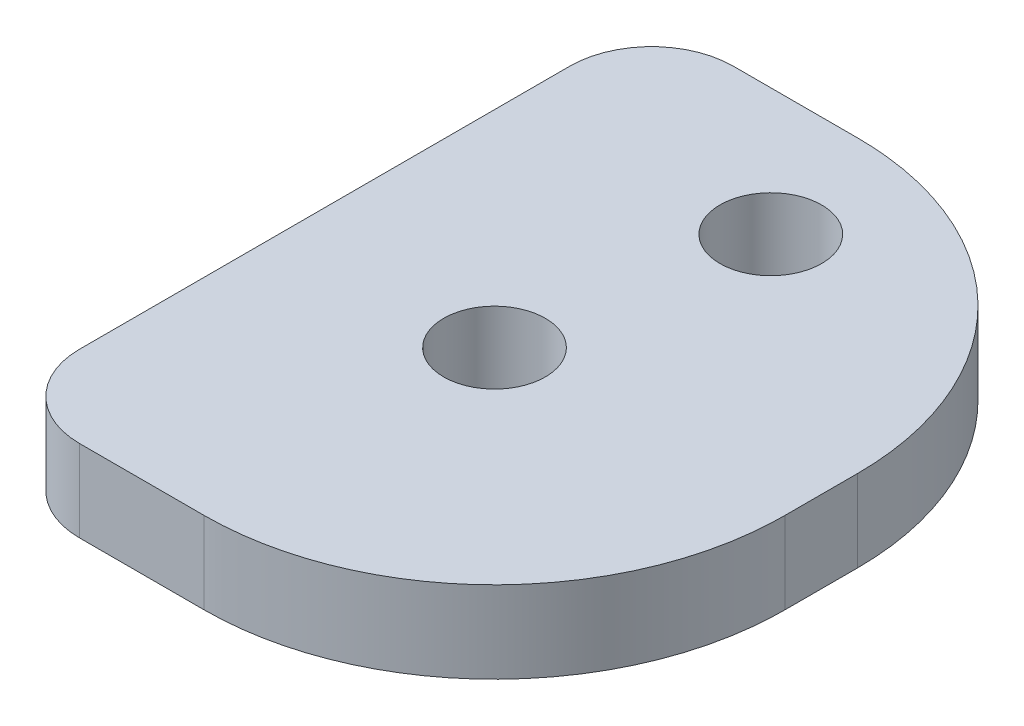
SolidWorks part; units mm, degrees
ref_plane "Front Plane" through (0, 0, 0) normal (0, 0, 1) x (1, 0, 0)
ref_plane "Top Plane" through (0, 0, 0) normal (0, 1, 0) x (1, 0, 0)
ref_plane "Right Plane" through (0, 0, 0) normal (1, 0, 0) x (0, 0, -1)
sketch "Sketch1" plane through (0, 0, 0) normal (0, 1, 0) x (1, 0, 0)
  line L1 (-25.4, 11.43) -> (25.4, 11.43)
  line L2 (-25.4, 11.43) -> (-25.4, -11.43)
  line L3 (-25.4, -11.43) -> (25.4, -11.43)
  line L4 (25.4, 11.43) -> (25.4, -11.43)
  dimension "D1" = 22.86
  dimension "D2" = 50.8
  dimension "D3" = 11.43
  dimension "D4" = 25.4
extrude "Boss-Extrude1" add sketch "Sketch1" along normal blind 3.175
fillet "Fillet1" radius 10.16 2 edges at (-25.4, 1.5875, 11.43) (25.4, 1.5875, 11.43)
sketch "Sketch3" plane through (0, 3.175, 0) normal (0, 1, 0) x (1, 0, 0)
  line L0 (-7.7526, -1.27) -> (18.5521, -1.27) construction
  circle A0 centre (15.24, -1.27) radius 1.778
  circle A1 centre (16.637, 6.9948) radius 1.778
  arc A2 (15.24, -11.43) -> (25.4, -1.27) centre (15.24, -1.27) ccw construction
  circle A3 centre (-3.81, -1.27) radius 1.778
  dimension "D1" = 3.556
  dimension "D2" = 3.556
  dimension "D6" = 3.556
  dimension "D3" = 8.382
  dimension "D4" = 1.397
  dimension "D5" = 19.05
extrude "Cut-Extrude1" cut sketch "Sketch3" against normal through all
fillet "Fillet3" radius 10.16 2 edges at (-25.4, 1.5875, -11.43) (25.4, 1.5875, -11.43)
scale "Scale1" scale about centroid uniform scaling no x scale factor 1.11 y scale factor 1 z scale factor 1.11
sketch "Sketch4" plane through (0, 3.175, 0) normal (0, 1, 0) x (1, 0, 0)
  line L1 (16.9458, 12.692) -> (-16.887, 12.692) construction
  line L2 (8.9448, 9.517) -> (8.9448, -9.5076) construction
  line L4 (-28.1646, 1.4144) -> (-28.1646, -1.405) construction
  line L5 (8.9448, 12.692) -> (-28.1646, 12.692)
  line L6 (8.9448, 12.692) -> (8.9448, -12.6826)
  line L7 (8.9448, -12.6826) -> (-28.1646, -12.6826)
  line L8 (-28.1646, 12.692) -> (-28.1646, -12.6826)
  line L9 (-16.887, -12.6826) -> (16.9458, -12.6826) construction
extrude "Cut-Extrude2" cut sketch "Sketch4" against normal through all contours L5 L8 L7 L6
fillet "Fillet4" radius 3.175 2 edges at (8.9448, 1.5875, 12.6826) (8.9448, 1.5875, -12.692)
equation "\"D4@Sketch1\"=\"D2@Sketch1\"/2"
equation "\"D3@Sketch1\"=\"D1@Sketch1\"/2"
